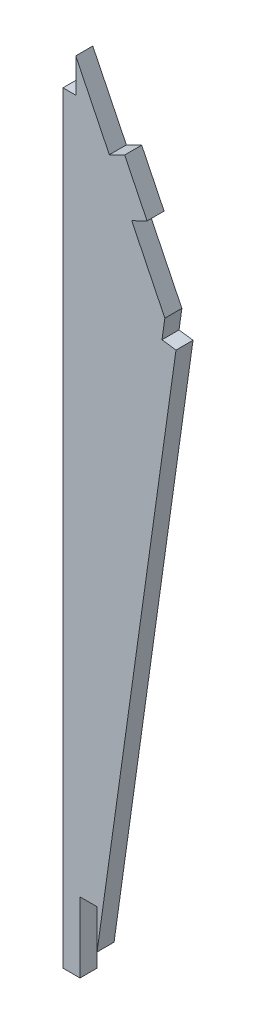
SolidWorks part; units mm, degrees
ref_plane "前视基准面" through (0, 0, 0) normal (0, 0, 1) x (1, 0, 0)
ref_plane "上视基准面" through (0, 0, 0) normal (0, 1, 0) x (1, 0, 0)
ref_plane "右视基准面" through (0, 0, 0) normal (1, 0, 0) x (0, 0, -1)
sketch "草图1" plane through (0, 0, 0) normal (0, 0, 1) x (1, 0, 0)
  line L0 (6.495, 96.8888) -> (6.495, 92.8888)
  line L1 (6.495, 92.8888) -> (4.995, 92.8888)
  line L2 (4.995, 92.8888) -> (4.995, 3.3395)
  line L3 (4.995, 3.3395) -> (6.995, 3.3395)
  line L4 (6.995, 3.3395) -> (6.995, 11.5895)
  line L5 (6.995, 11.5895) -> (8.995, 11.5895)
  line L6 (8.995, 11.5895) -> (8.995, 6.9812)
  line L7 (8.995, 6.9812) -> (18.268, 72.8462)
  line L8 (18.268, 72.8462) -> (16.6265, 73.0774)
  line L9 (16.6265, 73.0774) -> (16.9585, 75.4353)
  line L10 (6.495, 96.8888) -> (10.4403, 88.7997)
  line L11 (10.4403, 88.7997) -> (12.2379, 89.6764)
  line L12 (12.2379, 89.6764) -> (14.8681, 84.2836)
  line L13 (14.8681, 84.2836) -> (13.0705, 83.4069)
  line L14 (13.0705, 83.4069) -> (16.9585, 75.4353)
extrude "凸台-拉伸1" add sketch "草图1" along normal blind 2
